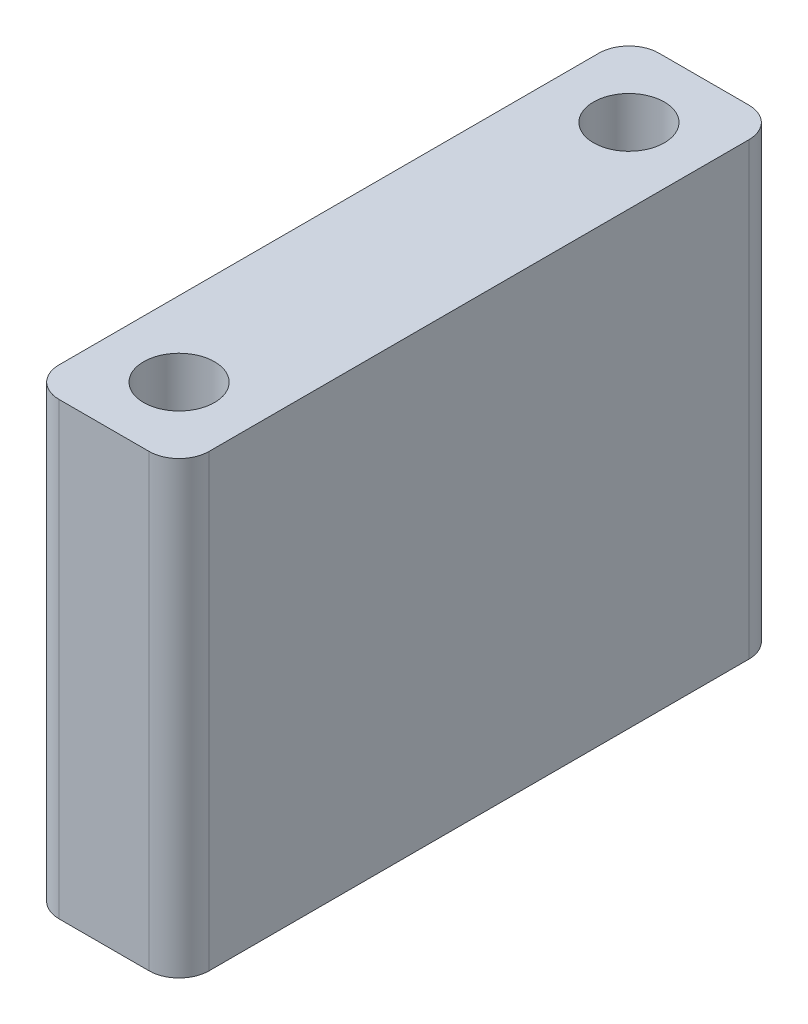
SolidWorks part; units mm, degrees
ref_plane "Front Plane" through (0, 0, 0) normal (0, 0, 1) x (1, 0, 0)
ref_plane "Top Plane" through (0, 0, 0) normal (0, 1, 0) x (1, 0, 0)
ref_plane "Right Plane" through (0, 0, 0) normal (1, 0, 0) x (0, 0, -1)
sketch "Sketch2" plane through (0, 0, 0) normal (0, 1, 0) x (1, 0, 0)
  line L0 (-19.05, 19.05) -> (-19.05, -19.05) construction
  line L1 (-22.86, -25.4) -> (22.86, -25.4)
  line L2 (-25.4, -22.86) -> (-25.4, 22.86)
  line L3 (-22.86, 25.4) -> (22.86, 25.4)
  line L4 (25.4, -22.86) -> (25.4, 22.86)
  line L5 (-25.4, -25.4) -> (25.4, 25.4) construction
  line L6 (-25.4, 25.4) -> (25.4, -25.4) construction
  line L7 (-25.4, 25.4) -> (-19.05, 25.4)
  line L8 (-25.4, 25.4) -> (-25.4, 19.05)
  line L9 (-25.4, 19.05) -> (-19.05, 19.05) construction
  line L10 (-19.05, 25.4) -> (-19.05, 19.05) construction
  line L11 (-12.7, -22.86) -> (-12.7, 22.86)
  circle A0 centre (-19.05, 19.05) radius 2.05
  circle A1 centre (0, 0) radius 6.35
  circle A2 centre (19.05, 19.05) radius 2.05
  circle A3 centre (19.05, -19.05) radius 2.05
  circle A4 centre (-19.05, -19.05) radius 2.05
  arc A5 (-22.86, -25.4) -> (-25.4, -22.86) centre (-22.86, -22.86) cw
  arc A6 (22.86, -25.4) -> (25.4, -22.86) centre (22.86, -22.86) ccw
  arc A7 (22.86, 25.4) -> (25.4, 22.86) centre (22.86, 22.86) cw
  arc A8 (-25.4, 22.86) -> (-22.86, 25.4) centre (-22.86, 22.86) cw
  arc A9 (-15.24, -25.4) -> (-12.7, -22.86) centre (-15.24, -22.86) ccw
  arc A10 (-12.7, 22.86) -> (-15.24, 25.4) centre (-15.24, 22.86) ccw
  point P0 (0, 0)
  dimension "D5" = 4.1
  dimension "D6" = 12.7
  dimension "D9" = 2.54
  dimension "D1" = 50.8
  dimension "D2" = 50.8
  dimension "D3" = 6.35
  dimension "D4" = 6.35
  dimension "D7" = 2
  dimension "D8" = 2
extrude "Boss-Extrude1" add sketch "Sketch2" along normal blind 38.1 contours A8 L2 A5 L1 A6 L4 A7 L3 A4 A3 A2 A1 A0
sketch "Sketch3" plane through (0, 38.1, 0) normal (0, 1, 0) x (1, 0, 0)
  circle A0 centre (-19.05, 19.05) radius 3
  circle A1 centre (-19.05, -19.05) radius 3
  dimension "D1" = 6
  dimension "D2" = 6
extrude "Cut-Extrude1" cut sketch "Sketch3" against normal blind 50
